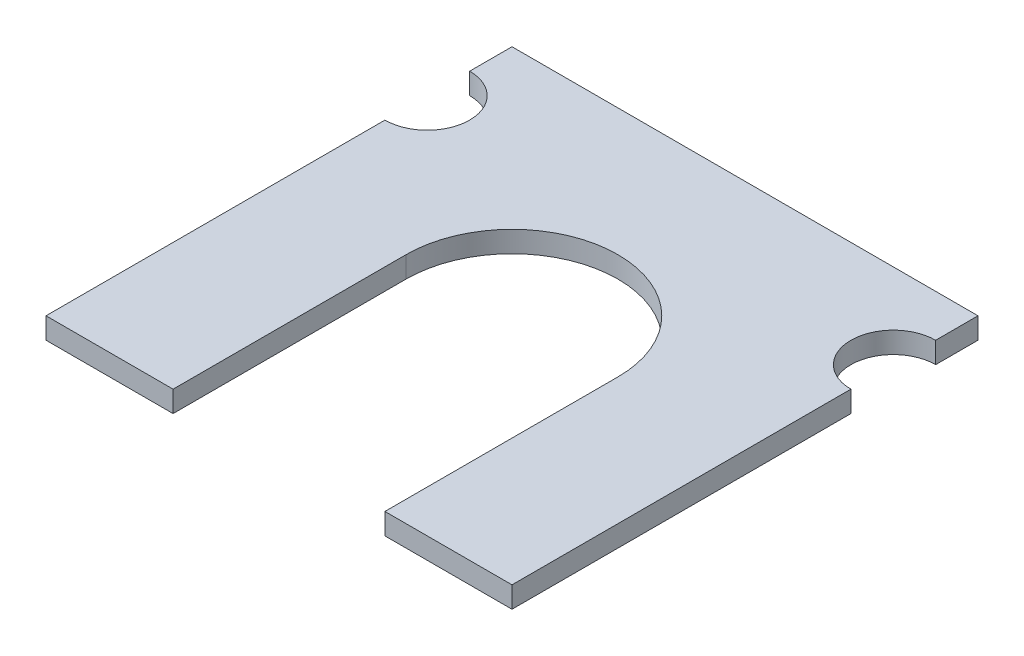
SolidWorks part; units mm, degrees
ref_plane "Front" through (0, 0, 0) normal (0, 0, 1) x (1, 0, 0)
ref_plane "Top" through (0, 0, 0) normal (0, 1, 0) x (1, 0, 0)
ref_plane "Right" through (0, 0, 0) normal (1, 0, 0) x (0, 0, -1)
sketch "Sketch1" plane through (0, 0, 0) normal (0, 1, 0) x (1, 0, 0)
  line L0 (-5.5, 5.5) -> (-5.5, 4.5)
  line L1 (-5.5, 5.5) -> (5.5, 5.5)
  line L2 (5.5, 5.5) -> (5.5, 4.5)
  line L3 (-2.5, 0) -> (-2.5, -5.5)
  line L4 (-2.5, -5.5) -> (-5.5, -5.5)
  line L5 (2.5, 0) -> (2.5, -5.5)
  line L6 (2.5, -5.5) -> (5.5, -5.5)
  line L7 (0, -0.8952) -> (0, -2.6757) construction
  line L8 (-5.5, 2.5) -> (-5.5, -5.5)
  line L9 (5.5, 2.5) -> (5.5, -5.5)
  arc A0 (2.5, 0) -> (-2.5, 0) centre (0, 0) ccw
  circle A1 centre (0, 0) radius 5.5 construction
  arc A2 (-5.5, 2.5) -> (-5.5, 4.5) centre (-5.5, 3.5) ccw
  arc A3 (5.5, 2.5) -> (5.5, 4.5) centre (5.5, 3.5) cw
  point P15 (-5.5, 3.5307)
  dimension "D1" = 5
  dimension "D2" = 11
  dimension "D3" = 2
  dimension "D4" = 1
extrude "Boss-Extrude1" add sketch "Sketch1" along normal blind 0.5
pattern_linear "LPattern1" [suppressed] count 19 spacing 11.25 count 11 spacing 11.25
